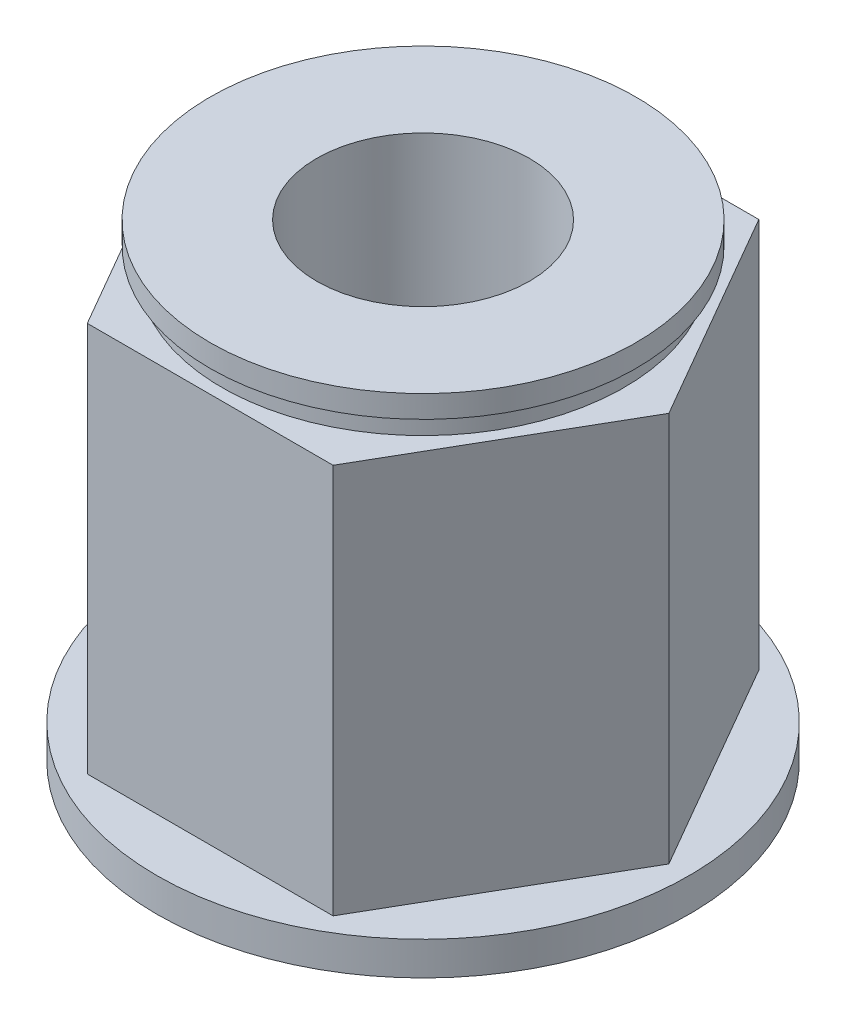
SolidWorks part; units mm, degrees
ref_plane "Front Plane" through (0, 0, 0) normal (0, 0, 1) x (1, 0, 0)
ref_plane "Top Plane" through (0, 0, 0) normal (0, 1, 0) x (1, 0, 0)
ref_plane "Right Plane" through (0, 0, 0) normal (1, 0, 0) x (0, 0, -1)
ref_plane "Plane1" through (0, 0, 0) normal (0, 0, -1) x (-1, 0, 0)
sketch "Sketch1" plane through (0, 0, 0) normal (0, 0, -1) x (-1, 0, 0)
  line L0 (-11.9062, -1.5) -> (0, -1.5)
  line L1 (0, -1.5) -> (0, 0)
  line L2 (0, 0) -> (-11.9062, 0)
  line L3 (-11.9062, 0) -> (-11.9062, -1.5)
  line L4 (0, -1.5) -> (0, 0) construction
revolve "Revolve1" add sketch "Sketch1" angle 360 about L4
sketch "Sketch2" plane through (0, 0, 0) normal (0, 1, 0) x (-1, 0, 0)
  line L0 (10.9985, 0) -> (5.4993, -9.525)
  line L1 (5.4993, -9.525) -> (-5.4993, -9.525)
  line L2 (-5.4993, -9.525) -> (-10.9985, 0)
  line L3 (-10.9985, 0) -> (-5.4993, 9.525)
  line L4 (-5.4993, 9.525) -> (5.4993, 9.525)
  line L5 (5.4993, 9.525) -> (10.9985, 0)
extrude "Boss-Extrude1" add sketch "Sketch2" along normal blind 17.4625
sketch "Sketch3" plane through (0, 0, 0) normal (0, 0, 1) x (1, 0, 0)
  line L0 (9, 18.4625) -> (0, 18.4625)
  line L1 (0, 18.4625) -> (0, 17.4625)
  line L2 (0, 17.4625) -> (9, 17.4625)
  line L3 (9, 17.4625) -> (9, 18.4625)
  line L4 (0, 18.4625) -> (0, 17.4625) construction
revolve "Revolve2" add sketch "Sketch3" angle 360 about L4
sketch "Sketch6" plane through (0, 18.4625, 0) normal (0, 1, 0) x (1, 0, 0)
  circle A0 centre (0, 0) radius 9.525
extrude "Boss-Extrude2" add sketch "Sketch6" along normal blind 1
hole_wizard "M8 Clearance Hole1" positions "Sketch5" profile "Sketch4" hole size "M8" standard "ANSI Metric"
sketch "Sketch5" plane through (0, -1.5, 0) normal (0, -1, 0) x (-1, 0, 0)
  point P0 (0, 0)
sketch "Sketch4" plane through (0, -1.5, 0) normal (1, 0, 0) x (0, 0, -1)
  line L0 (0, 0) -> (0, 23.8231)
  line L1 (0, 23.8231) -> (4.7625, 20.9615)
  line L2 (4.7625, 20.9615) -> (4.7625, 0)
  line L5 (4.7625, 0) -> (0, 0)
  line L10 (0, 23.8231) -> (-4.7625, 20.9615) construction
  line L11 (0, -6.35) -> (0, 107.95) construction
  dimension "Hole Dia." = 9.525
  dimension "Hole Depth" = 20.9615
  dimension "Drill Angle" = 118
